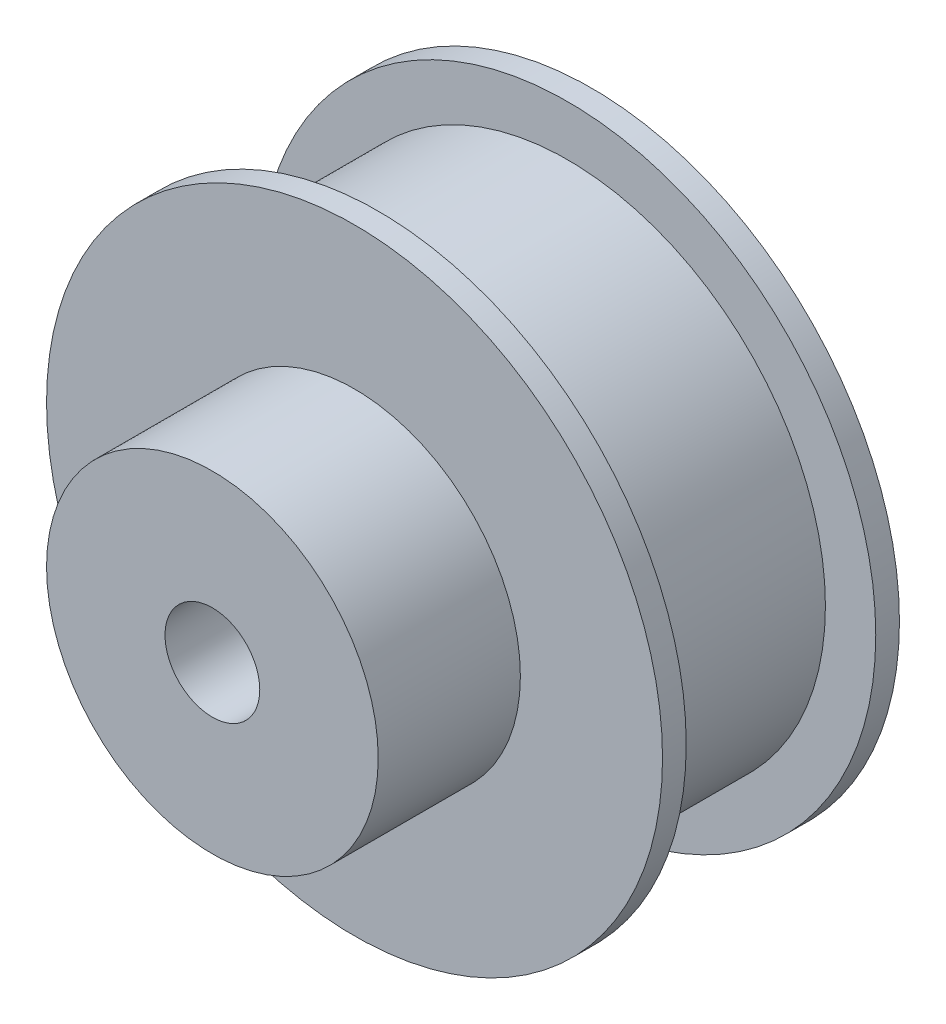
SolidWorks part; units mm, degrees
ref_plane "Plan de face" through (0, 0, 0) normal (0, 0, 1) x (1, 0, 0)
ref_plane "Plan de dessus" through (0, 0, 0) normal (0, 1, 0) x (1, 0, 0)
ref_plane "Plan de droite" through (0, 0, 0) normal (1, 0, 0) x (0, 0, -1)
sketch "Esquisse1" plane through (0, 0, 0) normal (0, 0, 1) x (1, 0, 0)
  circle A0 centre (0, 0) radius 13
extrude "Extrusion1" add sketch "Esquisse1" along normal blind 1
sketch "Esquisse2" plane through (0, 0, 1) normal (0, 0, 1) x (1, 0, 0)
  circle A0 centre (0, 0) radius 10.875
  dimension "D1" = 21.75
extrude "Extrusion2" add sketch "Esquisse2" along normal blind 8
sketch "Esquisse3" plane through (0, 0, 9) normal (0, 0, 1) x (1, 0, 0)
  circle A0 centre (0, 0) radius 13
extrude "Extrusion3" add sketch "Esquisse3" along normal blind 1
sketch "Esquisse4" plane through (0, 0, 10) normal (0, 0, 1) x (1, 0, 0)
  circle A0 centre (0, 0) radius 7
extrude "Extrusion4" add sketch "Esquisse4" along normal blind 6
sketch "Esquisse5" plane through (0, 0, 16) normal (0, 0, 1) x (1, 0, 0)
  circle A0 centre (0, 0) radius 2
extrude "Extrusion5" cut sketch "Esquisse5" against normal through all
